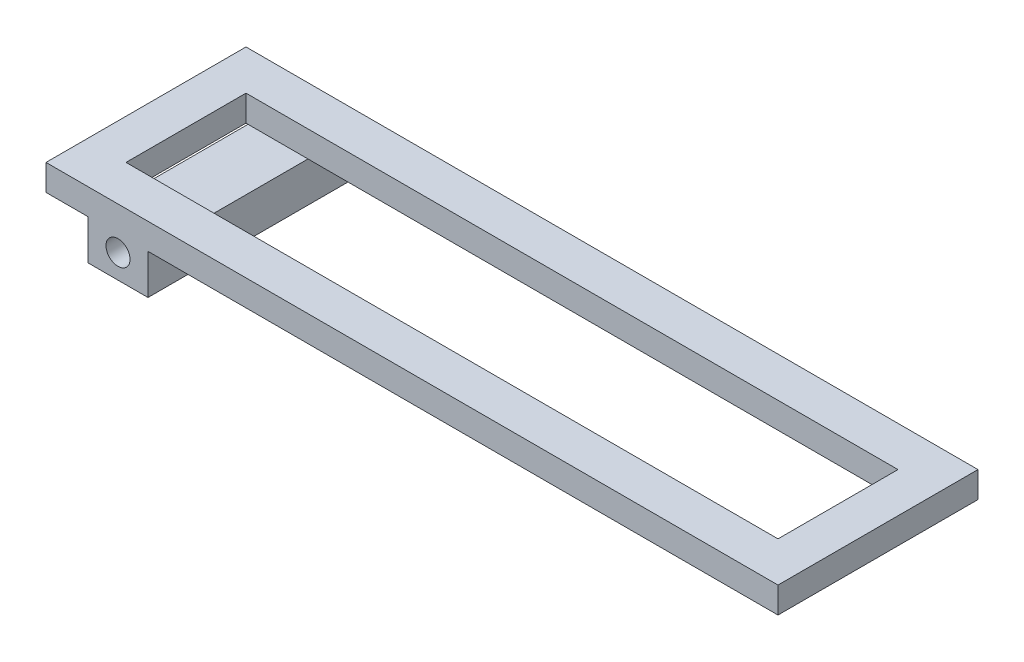
SolidWorks part; units mm, degrees
ref_plane "前视基准面" through (0, 0, 0) normal (0, 0, 1) x (1, 0, 0)
ref_plane "上视基准面" through (0, 0, 0) normal (0, 1, 0) x (1, 0, 0)
ref_plane "右视基准面" through (0, 0, 0) normal (1, 0, 0) x (0, 0, -1)
sketch "草图1" plane through (0, 0, 0) normal (0, 0, 1) x (1, 0, 0)
  line L1 (0, 0) -> (183, 0)
  line L2 (0, 0) -> (0, 6.5)
  line L3 (0, 6.5) -> (183, 6.5)
  line L4 (183, 0) -> (183, 6.5)
  dimension "D1" = 183
  dimension "D2" = 6.5
extrude "凸台-拉伸1" add sketch "草图1" against normal blind 10 contours L2 L1 L4 L3
sketch "草图2" plane through (0, 0, -10) normal (0, 0, -1) x (-1, 0, 0)
  line L0 (0, 0) -> (-183, 0) construction
  line L1 (-183, 6.5) -> (-173, 6.5)
  line L2 (-183, 6.5) -> (-183, 0)
  line L3 (-183, 0) -> (-173, 0)
  line L4 (-173, 6.5) -> (-173, 0)
  line L6 (0, 6.5) -> (-10, 6.5)
  line L7 (0, 6.5) -> (0, 0)
  line L8 (0, 0) -> (-10, 0)
  line L9 (-10, 6.5) -> (-10, 0)
  dimension "D1" = 10
  dimension "D2" = 10
extrude "凸台-拉伸2" add sketch "草图2" along normal blind 40
sketch "草图3" plane through (10, 0, 0) normal (1, 0, 0) x (0, 0, -1)
  line L0 (50, 0) -> (10, 0) construction
  line L1 (50, 6.5) -> (40, 6.5)
  line L2 (50, 6.5) -> (50, 0)
  line L3 (50, 0) -> (40, 0)
  line L4 (40, 6.5) -> (40, 0)
  dimension "D1" = 10
extrude "凸台-拉伸3" add sketch "草图3" along normal up to next
sketch "草图4" plane through (0, 0, 0) normal (0, -1, 0) x (1, 0, 0)
  line L0 (0, 0) -> (183, 0) construction
  line L1 (39.0711, 0) -> (59.0711, 0)
  line L2 (39.0711, 0) -> (39.0711, -50)
  line L3 (39.0711, -50) -> (59.0711, -50)
  line L4 (59.0711, 0) -> (59.0711, -50)
  line L5 (183, -50) -> (0, -50) construction
  point P8 (0, 0)
  dimension "D1" = 20
sketch "草图7" plane through (0, 0, 0) normal (0, -1, 0) x (1, 0, 0)
  line L0 (0, 0) -> (183, 0) construction
  line L1 (10.5, 0) -> (25.5, 0)
  line L2 (10.5, 0) -> (10.5, -50)
  line L3 (10.5, -50) -> (25.5, -50)
  line L4 (25.5, 0) -> (25.5, -50)
  line L5 (183, -50) -> (0, -50) construction
  line L6 (18, 0) -> (18, -50) construction
  line L7 (0, -50) -> (0, 0) construction
  point P12 (0, -25)
  dimension "D1" = 15
  dimension "D2" = 18
extrude "凸台-拉伸5" add sketch "草图7" along normal blind 10 contours L2 L1 L4 L3
sketch "草图8" plane through (0, 0, 0) normal (0, 0, 1) x (1, 0, 0)
  line L0 (18, -10) -> (18, 0) construction
  line L1 (10.5, -10) -> (25.5, -10) construction
  line L2 (0, 0) -> (10.5, 0) construction
  circle A0 centre (18, -4) radius 3
  point P6 (0, 0)
  dimension "D1" = 6
  dimension "D2" = 4
extrude "切除-拉伸2" cut sketch "草图8" against normal up to next
